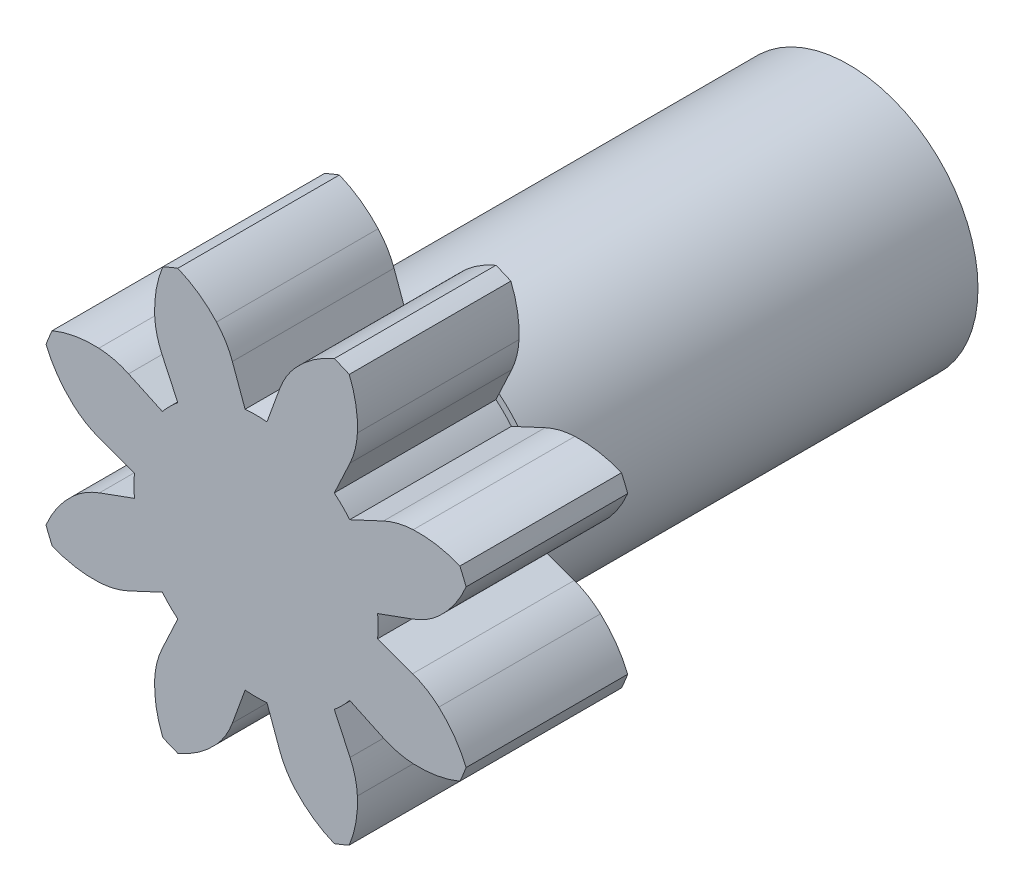
SolidWorks part; units mm, degrees
ref_plane "Plano frontal" through (0, 0, 0) normal (0, 0, 1) x (1, 0, 0)
ref_plane "Plano superior" through (0, 0, 0) normal (0, 1, 0) x (1, 0, 0)
ref_plane "Plano direito" through (0, 0, 0) normal (1, 0, 0) x (0, 0, -1)
sketch "Esboço2" plane through (0, 0, 0) normal (0, 0, 1) x (1, 0, 0)
  circle A0 centre (0, 0) radius 10.4
  dimension "D1" = 20.8
extrude "Ressalto-extrusão1" add sketch "Esboço2" along normal blind 7.5
sketch "Esboço1" plane through (0, 0, 0) normal (0, 0, 1) x (1, 0, 0)
  line L0 (0, 0) -> (0, 12.5255) construction
  line L1 (-0.5068, 5.6423) -> (0, 4.25) construction
  line L2 (-0.5068, 5.6423) -> (-1.0979, 7.2665)
  line L3 (0.5068, 5.6423) -> (1.0979, 7.2665)
  circle A0 centre (0, 0) radius 10.4 construction
  circle A1 centre (0, 0) radius 7.54 construction
  circle A2 centre (0, 0) radius 5.665 construction
  circle A3 centre (0, 0) radius 4.25 construction
  arc A4 (-3.6301, 9.7459) -> (-1.833, 8.4832) centre (-5.5475, 5.1065) cw
  arc A5 (1.833, 8.4832) -> (1.0979, 7.2665) centre (4.556, 6.0079) ccw
  arc A6 (-1.833, 8.4832) -> (-1.0979, 7.2665) centre (-4.556, 6.0079) cw
  arc A7 (3.6301, 9.7459) -> (1.833, 8.4832) centre (5.5475, 5.1065) ccw
  arc A8 (-0.5068, 5.6423) -> (0.5068, 5.6423) centre (0, 0) cw
  arc A9 (-3.6301, 9.7459) -> (3.6301, 9.7459) centre (0, 0) cw
  dimension "D1" = 20.8
  dimension "D2" = 15.08
  dimension "D3" = 11.33
  dimension "D4" = 8.5
  dimension "D7" = 5.02
  dimension "D8" = 3.68
  dimension "D5" = 20
extrude "Corte-extrusão1" cut sketch "Esboço1" along normal through all
pattern_circular "PadrãoCircular2" count 8 over 360 about axis through (0, 0, 0) along (0, 0, 1) of "Corte-extrusão1"
sketch "Esboço3" plane through (0, 0, 0) normal (0, 0, -1) x (-1, 0, 0)
  circle A0 centre (0, 0) radius 6
  dimension "D1" = 12
extrude "Ressalto-extrusão2" add sketch "Esboço3" along normal blind 20
